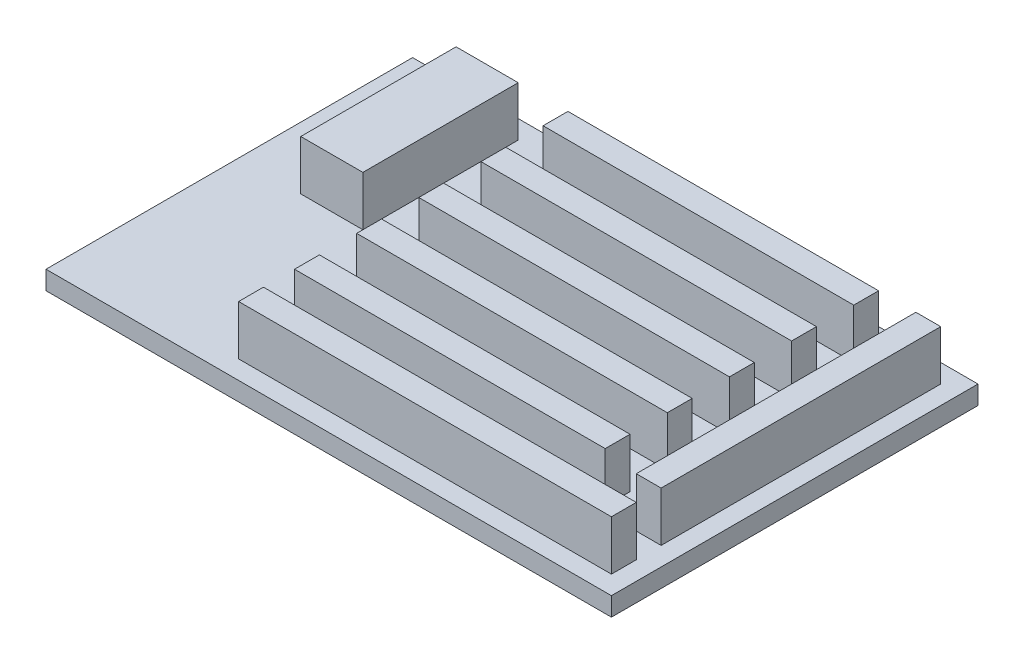
SolidWorks part; units mm, degrees
ref_plane "Front Plane" through (0, 0, 0) normal (0, 0, 1) x (1, 0, 0)
ref_plane "Top Plane" through (0, 0, 0) normal (0, 1, 0) x (1, 0, 0)
ref_plane "Right Plane" through (0, 0, 0) normal (1, 0, 0) x (0, 0, -1)
sketch "Sketch1" plane through (0, 0, 0) normal (0, 1, 0) x (1, 0, 0)
  line L1 (0, 0) -> (91, 0)
  line L2 (0, 0) -> (0, 59)
  line L3 (0, 59) -> (91, 59)
  line L4 (91, 0) -> (91, 59)
  dimension "D1" = 91
  dimension "D2" = 59
extrude "Boss-Extrude1" add sketch "Sketch1" along normal blind 3
sketch "Sketch2" plane through (0, 3, 0) normal (0, 1, 0) x (1, 0, 0)
  line L0 (0, 0) -> (91, 0) construction
  line L1 (10, 56) -> (20, 56)
  line L2 (10, 56) -> (10, 31)
  line L3 (10, 31) -> (20, 31)
  line L4 (20, 56) -> (20, 31)
  line L5 (28, 56) -> (78, 56)
  line L6 (28, 56) -> (28, 52)
  line L7 (28, 52) -> (78, 52)
  line L8 (78, 56) -> (78, 52)
  line L9 (84, 56) -> (88, 56)
  line L10 (84, 56) -> (84, 11)
  line L11 (84, 11) -> (88, 11)
  line L12 (88, 56) -> (88, 11)
  line L13 (28, 7) -> (88, 7)
  line L14 (28, 7) -> (28, 3)
  line L15 (28, 3) -> (88, 3)
  line L16 (88, 7) -> (88, 3)
  line L17 (91, 59) -> (0, 59) construction
  line L18 (0, 59) -> (0, 0) construction
  line L19 (91, 0) -> (91, 59) construction
  line L20 (28, 46) -> (28, 42)
  line L21 (28, 46) -> (78, 46)
  line L22 (78, 46) -> (78, 42)
  line L23 (28, 42) -> (78, 42)
  line L24 (28, 36) -> (28, 32)
  line L25 (28, 36) -> (78, 36)
  line L26 (78, 36) -> (78, 32)
  line L27 (28, 32) -> (78, 32)
  line L28 (28, 26) -> (28, 22)
  line L29 (28, 26) -> (78, 26)
  line L30 (78, 26) -> (78, 22)
  line L31 (28, 22) -> (78, 22)
  line L32 (28, 16) -> (28, 12)
  line L33 (28, 16) -> (78, 16)
  line L34 (78, 16) -> (78, 12)
  line L35 (28, 12) -> (78, 12)
  point P22 (86, 56)
  point P25 (86, 11)
  dimension "D1" = 3
  dimension "D2" = 3
  dimension "D3" = 10
  dimension "D4" = 25
  dimension "D5" = 45
  dimension "D6" = 50
  dimension "D7" = 6
  dimension "D8" = 4
  dimension "D9" = 3
  dimension "D10" = 10
  dimension "D11" = 5
extrude "Boss-Extrude2" add sketch "Sketch2" along normal blind 8
